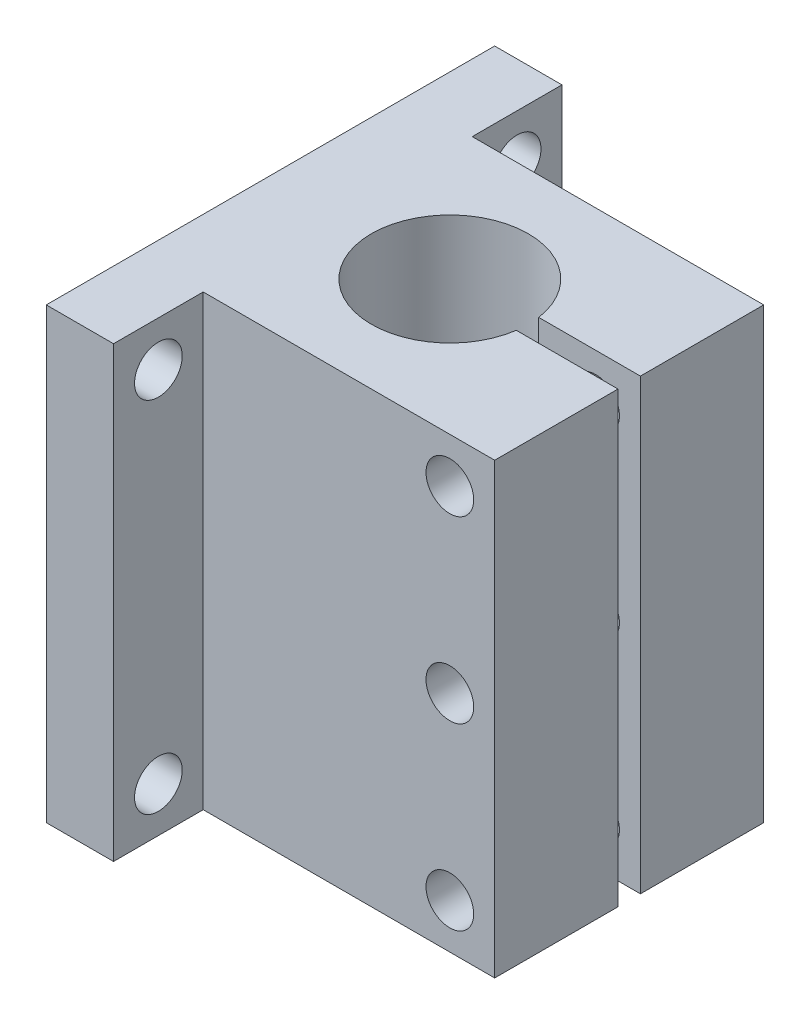
SolidWorks part; units mm, degrees
ref_plane "Front Plane" through (0, 0, 0) normal (0, 0, 1) x (1, 0, 0)
ref_plane "Top Plane" through (0, 0, 0) normal (0, 1, 0) x (1, 0, 0)
ref_plane "Right Plane" through (0, 0, 0) normal (1, 0, 0) x (0, 0, -1)
sketch "Sketch1" plane through (0, 0, 0) normal (0, 1, 0) x (1, 0, 0)
  line L1 (-25.4, 31.75) -> (25.4, 31.75)
  line L2 (-25.4, 31.75) -> (-25.4, -31.75)
  line L3 (-25.4, -31.75) -> (25.4, -31.75)
  line L4 (25.4, 31.75) -> (25.4, -31.75)
  line L5 (-25.4, 31.75) -> (25.4, -31.75) construction
  line L6 (-25.4, -31.75) -> (25.4, 31.75) construction
  point P0 (0, 0)
  dimension "D1" = 50.8
  dimension "D2" = 63.5
extrude "Boss-Extrude1" add sketch "Sketch1" along normal blind 63.5
sketch "Sketch2" plane through (0, 63.5, 0) normal (0, 1, 0) x (1, 0, 0)
  circle A0 centre (0, 0) radius 11.1125
  dimension "D1" = 22.225
extrude "Cut-Extrude1" cut sketch "Sketch2" against normal through all
sketch "Sketch3" plane through (0, 63.5, 0) normal (0, 1, 0) x (1, 0, 0)
  line L0 (-25.4, -31.75) -> (25.4, -31.75) construction
  line L1 (25.4, 31.75) -> (-15.875, 31.75)
  line L2 (25.4, 31.75) -> (25.4, 19.05)
  line L3 (25.4, 19.05) -> (-15.875, 19.05)
  line L4 (-15.875, 31.75) -> (-15.875, 19.05)
  line L5 (-15.875, -31.75) -> (25.4, -31.75)
  line L6 (-15.875, -31.75) -> (-15.875, -19.05)
  line L7 (-15.875, -19.05) -> (25.4, -19.05)
  line L8 (25.4, -31.75) -> (25.4, -19.05)
  line L9 (25.4, -31.75) -> (25.4, 31.75) construction
  line L10 (-25.4, 31.75) -> (-25.4, -31.75) construction
  dimension "D1" = 9.525
  dimension "D2" = 12.7
extrude "Cut-Extrude2" cut sketch "Sketch3" against normal through all
hole_wizard "1/4 Clearance Hole1" positions "Sketch5" profile "Sketch4" hole size "1/4" standard "ANSI Inch"
sketch "Sketch5" plane through (-15.875, 0, 0) normal (1, 0, 0) x (0, 0, -1)
  line L13 (-25.4, 57.15) -> (25.4, 57.15) construction
  line L14 (-25.4, 57.15) -> (-25.4, 6.35) construction
  line L15 (-25.4, 6.35) -> (25.4, 6.35) construction
  line L16 (25.4, 57.15) -> (25.4, 6.35) construction
  line L17 (0, 6.35) -> (0, 0) construction
  line L19 (-19.05, 63.5) -> (-31.75, 63.5) construction
  line L20 (-31.75, 0) -> (-31.75, 63.5) construction
  point P303 (-25.4, 57.15)
  point P304 (25.4, 6.35)
  point P557 (-25.4, 6.35)
  point P558 (25.4, 57.15)
  dimension "D1" = 6.35
  dimension "D2" = 6.35
  dimension "D3" = 6.35
sketch "Sketch4" plane through (-15.875, 57.15, 25.4) normal (0, 1, 0) x (0, 0, -1)
  line L0 (0, 0) -> (0, 11.6818)
  line L1 (0, 11.6818) -> (3.3782, 9.652)
  line L2 (3.3782, 9.652) -> (3.3782, 0)
  line L5 (3.3782, 0) -> (0, 0)
  line L10 (0, 11.6818) -> (-3.3782, 9.652) construction
  line L11 (0, -6.35) -> (0, 107.95) construction
  dimension "Hole Dia." = 6.7564
  dimension "Hole Depth" = 9.652
  dimension "Drill Angle" = 118
sketch "Sketch6" plane through (25.4, 0, 0) normal (1, 0, 0) x (0, 0, -1)
  line L0 (-19.05, 0) -> (19.05, 0) construction
  line L1 (-1.5875, 0) -> (1.5875, 0)
  line L2 (-1.5875, 0) -> (-1.5875, 63.5)
  line L3 (-1.5875, 63.5) -> (1.5875, 63.5)
  line L4 (1.5875, 0) -> (1.5875, 63.5)
  line L5 (-19.05, 63.5) -> (19.05, 63.5) construction
  dimension "D1" = 3.175
extrude "Cut-Extrude3" cut sketch "Sketch6" against normal blind 24.13
hole_wizard "1/4 Clearance Hole2" positions "Sketch8" profile "Sketch9" hole size "1/4" standard "ANSI Inch" end condition through all
sketch "Sketch8" plane through (0, 0, 19.05) normal (0, 0, 1) x (1, 0, 0)
  line L0 (19.05, 63.5) -> (19.05, 0) construction
  line L1 (25.4, 63.5) -> (-15.875, 63.5) construction
  line L2 (25.4, 0) -> (-15.875, 0) construction
  line L3 (25.4, 0) -> (25.4, 63.5) construction
  point P9 (19.05, 57.15)
  point P11 (19.05, 31.75)
  point P13 (19.05, 6.35)
  dimension "D1" = 6.35
  dimension "D2" = 6.35
  dimension "D3" = 6.35
sketch "Sketch9" plane through (19.05, 57.15, 19.05) normal (1, 0, 0) x (0, -1, 0)
  line L0 (0, 0) -> (0, 50.8)
  line L1 (0, 50.8) -> (3.3782, 50.8)
  line L2 (3.3782, 50.8) -> (3.3782, 0)
  line L5 (3.3782, 0) -> (0, 0)
  line L11 (0, -6.35) -> (0, 107.95) construction
  dimension "Thru Hole Dia." = 6.7564
  dimension "Thru Hole Depth" = 50.8
